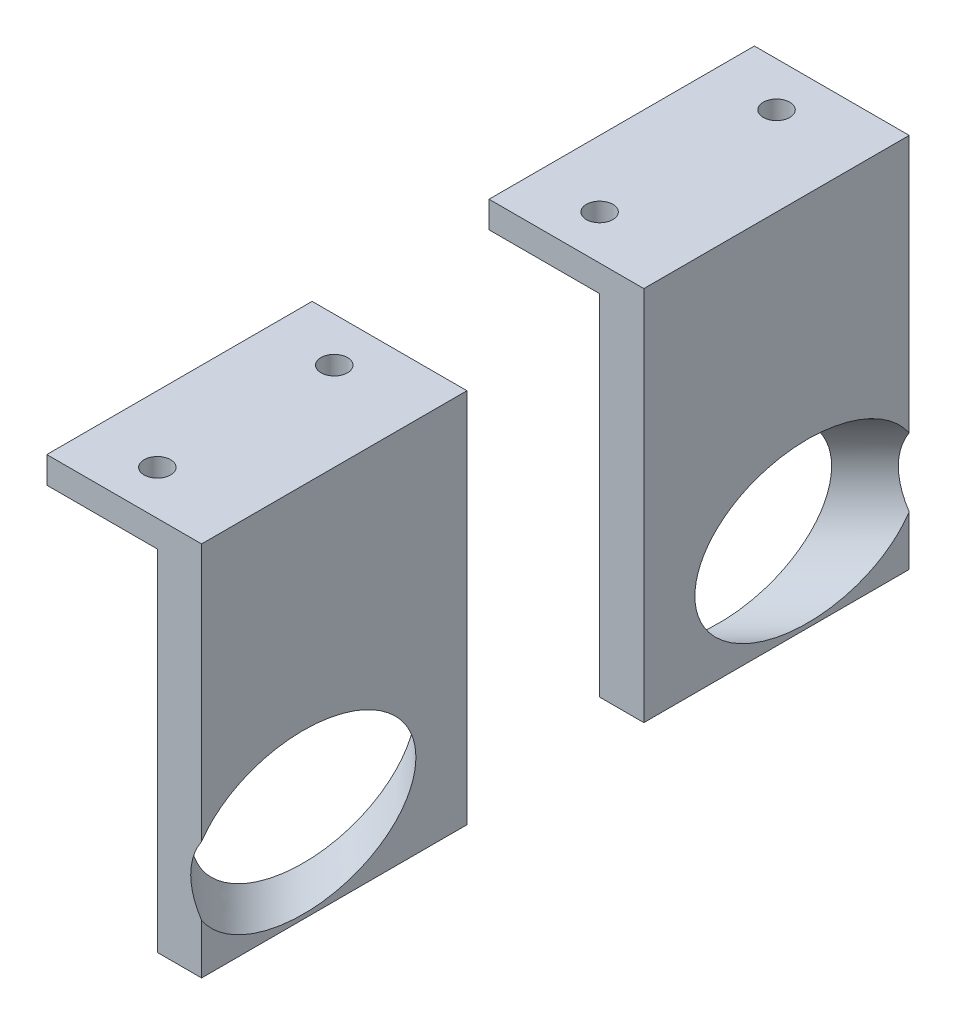
SolidWorks part; units mm, degrees
ref_plane "前视基准面" through (0, 0, 0) normal (0, 0, 1) x (1, 0, 0)
ref_plane "上视基准面" through (0, 0, 0) normal (0, 1, 0) x (1, 0, 0)
ref_plane "右视基准面" through (0, 0, 0) normal (1, 0, 0) x (0, 0, -1)
other "Configuration Table"
sketch "草图1" plane through (0, 0, 0) normal (1, 0, 0) x (0, 0, -1)
  line L0 (-15, -28.5) -> (-15, 11)
  line L2 (-15, 11) -> (15, 11)
  line L3 (15, -28.5) -> (15, 11)
  line L4 (-15, -28.5) -> (15, 11) construction
  line L5 (-15, 11) -> (15, -28.5) construction
  line L6 (-15, -28.5) -> (15, -28.5)
  point P0 (0, 0)
  point P2 (0, 0)
extrude "凸台-拉伸1" add sketch "草图1" along normal blind 5 contours L2 L3 L6 L0
sketch3d "3D草图1"
  point P0 (5, -2.7495, 2.7495)
ref_plane "基准面1" through (5, 0, 0) normal (1, 0, 0) x (0, 0, -1)
sketch3d "3D草图2"
  point P0 (2.9808, 11, -3.1847)
ref_plane "基准面2" through (0, 11, 0) normal (0, 1, 0) x (1, 0, 0)
sketch "草图3" plane through (0, 11, 0) normal (0, 1, 0) x (1, 0, 0)
  line L1 (5, -15) -> (-12.5, -15)
  line L2 (5, 15) -> (-12.5, 15)
  line L3 (-12.5, 15) -> (-12.5, -15)
  line L4 (5, 15) -> (5, -15)
extrude "凸台-拉伸2" add sketch "草图3" along normal blind 3
sketch3d "3D草图3"
  point P0 (-6.2094, 14, 4.3134)
ref_plane "基准面4" through (0, 14, 0) normal (0, 1, 0) x (1, 0, 0)
sketch "草图6" plane through (0, 14, 0) normal (0, 1, 0) x (1, 0, 0)
  circle A0 centre (-5, 10) radius 1.5
  circle A1 centre (-5, -10) radius 1.5
extrude "切除-拉伸2" cut sketch "草图6" against normal blind 3
sketch "草图7" plane through (0, 0, 0) normal (1, 0, 0) x (0, 0, -1)
  ellipse E0 centre (1.5, -19) end of major axis (-11.228, -19) minor radius 9
  point P0 (-46.6583, -10)
sketch "草图8" plane through (0, 0, 0) normal (0, 1, 0) x (1, 0, 0)
  line L0 (5, -15) -> (-18.8679, 8.8679)
extrude "切除-拉伸3" cut sketch "草图7" along direction (-0.7071, 0, -0.7071) on the side of the normal blind 10
ref_plane "基准面5" through (0, 0, -25) normal (0, 0, -1) x (-1, 0, 0)
mirror "镜向1" about plane through (0, 0, -25) normal (0, 0, -1) of bodies 111
